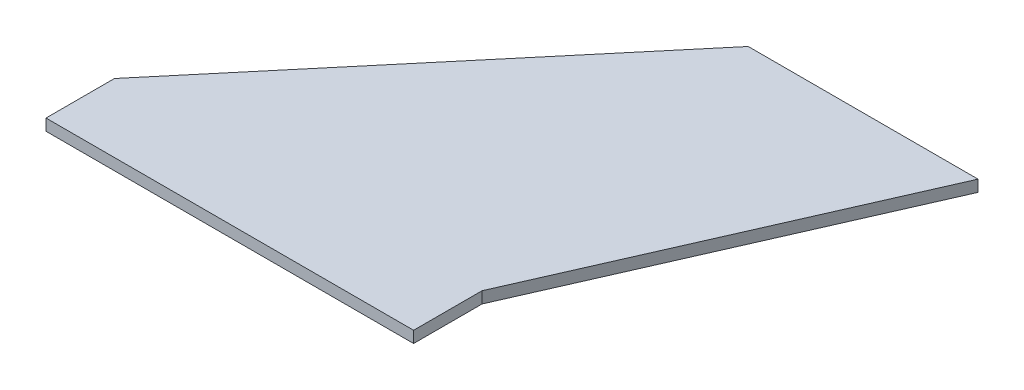
SolidWorks part; units mm, degrees
ref_plane "Front Plane" through (0, 0, 0) normal (0, 0, 1) x (1, 0, 0)
ref_plane "Top Plane" through (0, 0, 0) normal (0, 1, 0) x (1, 0, 0)
ref_plane "Right Plane" through (0, 0, 0) normal (1, 0, 0) x (0, 0, -1)
sketch "Sketch1" plane through (0, 0, 0) normal (0, 1, 0) x (1, 0, 0)
  line L0 (50.8, 0) -> (-50.8, 0) construction
  line L1 (-50.8, 0) -> (29.1242, 95.25)
  line L2 (29.1242, 95.25) -> (92.6242, 95.25)
  line L3 (92.6242, 95.25) -> (50.8, 0)
  line L4 (50.8, -18.923) -> (-50.8, -18.923)
  line L5 (-50.8, -18.923) -> (-50.8, 0)
  line L6 (50.8, 0) -> (50.8, -18.923)
  point P4 (0, 0)
  dimension "D1" = 18.923
  dimension "D2" = 101.6
  dimension "D3" = 63.5
  dimension "D4" = 95.25
  dimension "D5" = 40
extrude "Boss-Extrude1" add sketch "Sketch1" along normal blind 3.175
equation "\"kerf\"= 0.005"
equation "\"Sweep Angle\" = 40"
equation "\"Tab height\" = 0.745"
equation "\"Thicckness\" = 0.125"
equation "\"Tip Chord Length\" = 2.5"
equation "\"Root Chord Length\"=4"
equation "\"Height\" = 3.75"
equation "\"D4@Sketch1\"=\"Height\""
equation "\"D3@Sketch1\"=\"Tip Chord Length\""
equation "\"D2@Sketch1\"=\"Root Chord Length\""
equation "\"D1@Sketch1\"=\"Tab height\""
equation "\"D5@Sketch1\"=\"Sweep Angle\""
